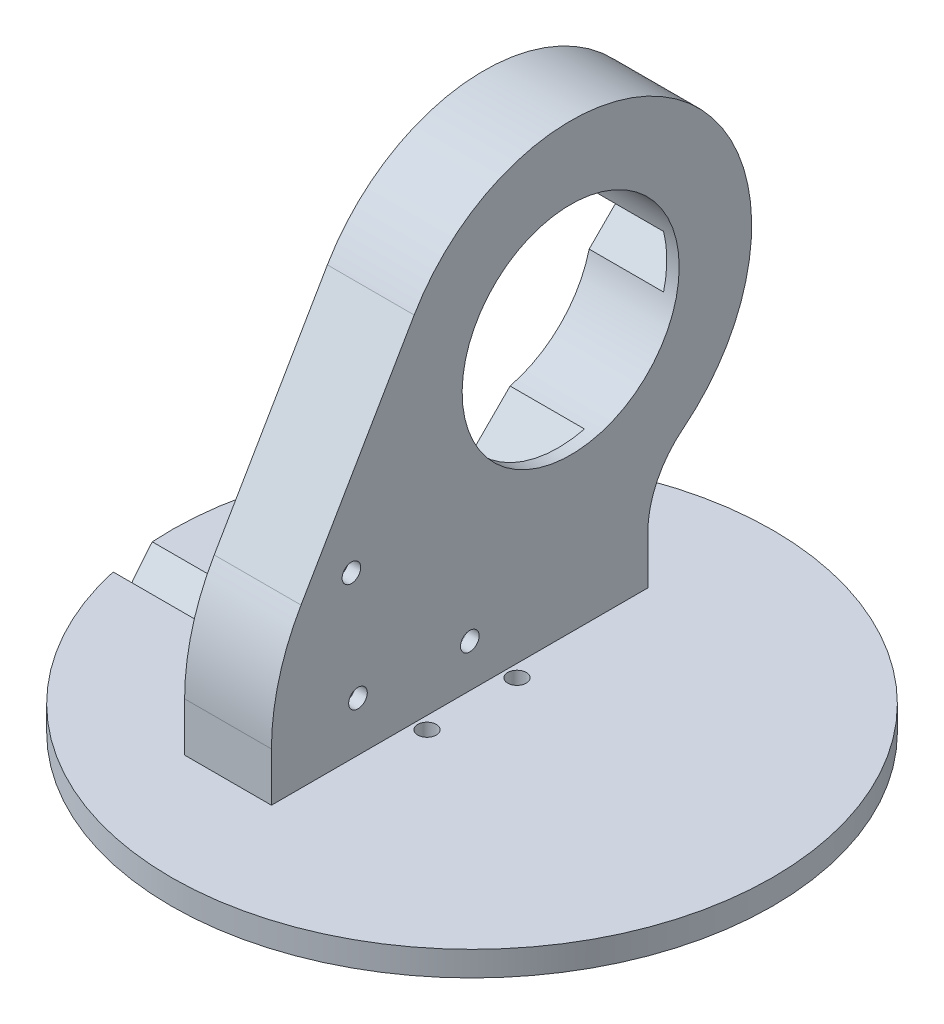
SolidWorks part; units mm, degrees
ref_plane "Front Plane" through (0, 0, 0) normal (0, 0, 1) x (1, 0, 0)
ref_plane "Top Plane" through (0, 0, 0) normal (0, 1, 0) x (1, 0, 0)
ref_plane "Right Plane" through (0, 0, 0) normal (1, 0, 0) x (0, 0, -1)
sketch "Sketch1" plane through (0, 0, 0) normal (0, 1, 0) x (1, 0, 0)
  line L0 (0, 7.25) -> (0, -7.25)
  circle A0 centre (0, 0) radius 48.5
  circle A1 centre (0, 7.25) radius 1.5
  circle A2 centre (0, -7.25) radius 1.5
  point P6 (0, 0)
  dimension "D2" = 97
  dimension "D3" = 3
  dimension "D1" = 14.5
extrude "Boss-Extrude1" add sketch "Sketch1" along normal blind 4
sketch "Sketch2" plane through (0, 4, 0) normal (0, 1, 0) x (1, 0, 0)
  circle A0 centre (0, 0) radius 3.75
  dimension "D1" = 7.5
sketch "Sketch3" plane through (0, 0, 0) normal (1, 0, 0) x (0, 0, -1)
  line L0 (-30.34, 4) -> (30.34, 4)
  line L1 (48.5, 4) -> (-48.5, 4) construction
  line L2 (30.34, 4) -> (30.34, 11.64)
  line L3 (-30.34, 4) -> (-30.34, 11.86)
  line L4 (-25.5664, 29.5677) -> (-7.3207, 60.9494)
  arc A0 (30.34, 11.64) -> (36.0281, 23.3996) centre (45.34, 11.64) cw
  arc A1 (36.0281, 23.3996) -> (-7.3207, 60.9494) centre (17.91, 46.28) ccw
  arc A2 (-30.34, 11.86) -> (-25.5664, 29.5677) centre (4.89, 11.86) cw
  circle A3 centre (17.91, 46.28) radius 17.5
  point P5 (0, 4)
  dimension "D3" = 15
  dimension "D5" = 35.23
  dimension "D6" = 35
  dimension "D1" = 60.68
  dimension "D2" = 7.64
  dimension "D4" = 7.86
  dimension "D7" = 17.91
  dimension "D8" = 46.28
extrude "Cut-Extrude2" cut sketch "Sketch2" against normal blind 1.5 from offset 2.5 offset against normal yes
extrude "Boss-Extrude2" add sketch "Sketch3" along normal blind 14 from offset 16 contours A3 offset against normal yes
sketch "Sketch6" plane through (0, 0, 0) normal (1, 0, 0) x (0, 0, -1)
  line L4 (-28.0519, 21.5313) -> (-6.8387, 0.3181)
  line L5 (-6.8387, 0.3181) -> (39.1232, 46.28)
  line L6 (-30.34, 4) -> (30.34, 4) construction
  line L8 (39.1232, 46.28) -> (17.91, 67.4932)
  line L9 (17.91, 67.4932) -> (-28.0519, 21.5313)
  circle A0 centre (17.91, 46.28) radius 15
  dimension "D1" = 30
  dimension "D4" = 45
  dimension "D2" = 30
  dimension "D3" = 65
extrude "Cut-Extrude3" cut sketch "Sketch6" against normal through all from offset 4 contours A0 L9 L4 L5 | A0 | A0 L5 L8 | A0 L8 L9 offset against normal yes
sketch "Sketch8" plane through (-4, 0, 0) normal (-1, 0, 0) x (0, 0, 1)
  line L0 (-17.91, 67.4932) -> (-39.1232, 46.28)
  line L1 (-39.1232, 46.28) -> (6.8387, 0.3181)
  line L2 (6.8387, 0.3181) -> (28.0519, 21.5313)
  line L3 (28.0519, 21.5313) -> (-17.91, 67.4932)
  line L4 (25.9306, 21.5313) -> (17.4453, 30.0165) construction
  line L5 (6.8387, 2.4394) -> (25.9306, 21.5313)
  line L6 (6.8387, 2.4394) -> (-1.6465, 10.9247)
  circle A0 centre (25.9306, 21.5313) radius 1.5
  circle A1 centre (17.4453, 30.0165) radius 1.5
  circle A2 centre (6.8387, 2.4394) radius 1.5
  circle A3 centre (16.3847, 11.9853) radius 1.5
  circle A4 centre (-1.6465, 10.9247) radius 1.5
  dimension "D1" = 3
  dimension "D2" = 3
  dimension "D4" = 3
  dimension "D6" = 3
  dimension "D3" = 12
  dimension "D5" = 12
extrude "Cut-Extrude4" cut sketch "Sketch8" against normal through all both and the other way through all
